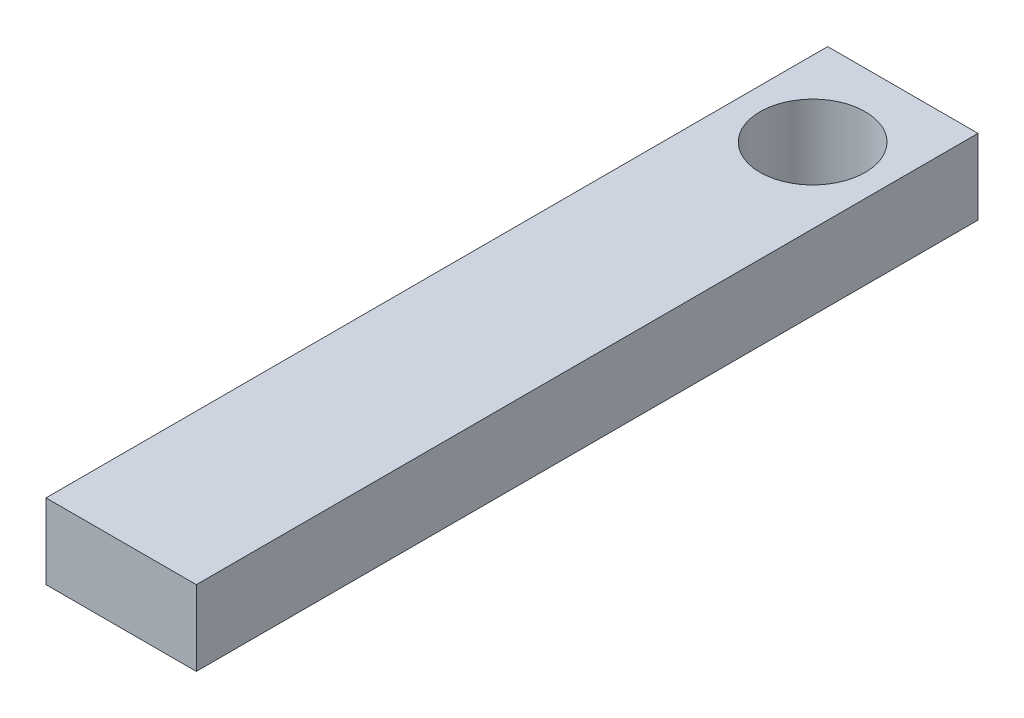
SolidWorks part; units mm, degrees
ref_plane "Front Plane" through (0, 0, 0) normal (0, 0, 1) x (1, 0, 0)
ref_plane "Top Plane" through (0, 0, 0) normal (0, 1, 0) x (1, 0, 0)
ref_plane "Right Plane" through (0, 0, 0) normal (1, 0, 0) x (0, 0, -1)
sketch "Sketch1" plane through (0, 0, 0) normal (0, 1, 0) x (1, 0, 0)
  line L0 (0, 52) -> (5, 46) construction
  line L1 (0, 0) -> (10, 0)
  line L2 (0, 0) -> (0, 52)
  line L3 (0, 52) -> (10, 52)
  line L4 (10, 0) -> (10, 52)
  line L5 (5, 46) -> (10, 52) construction
  circle A0 centre (5, 46) radius 3.5
  dimension "D3" = 7
  dimension "D1" = 52
  dimension "D2" = 10
  dimension "D4" = 6
extrude "Boss-Extrude1" add sketch "Sketch1" along normal blind 5
